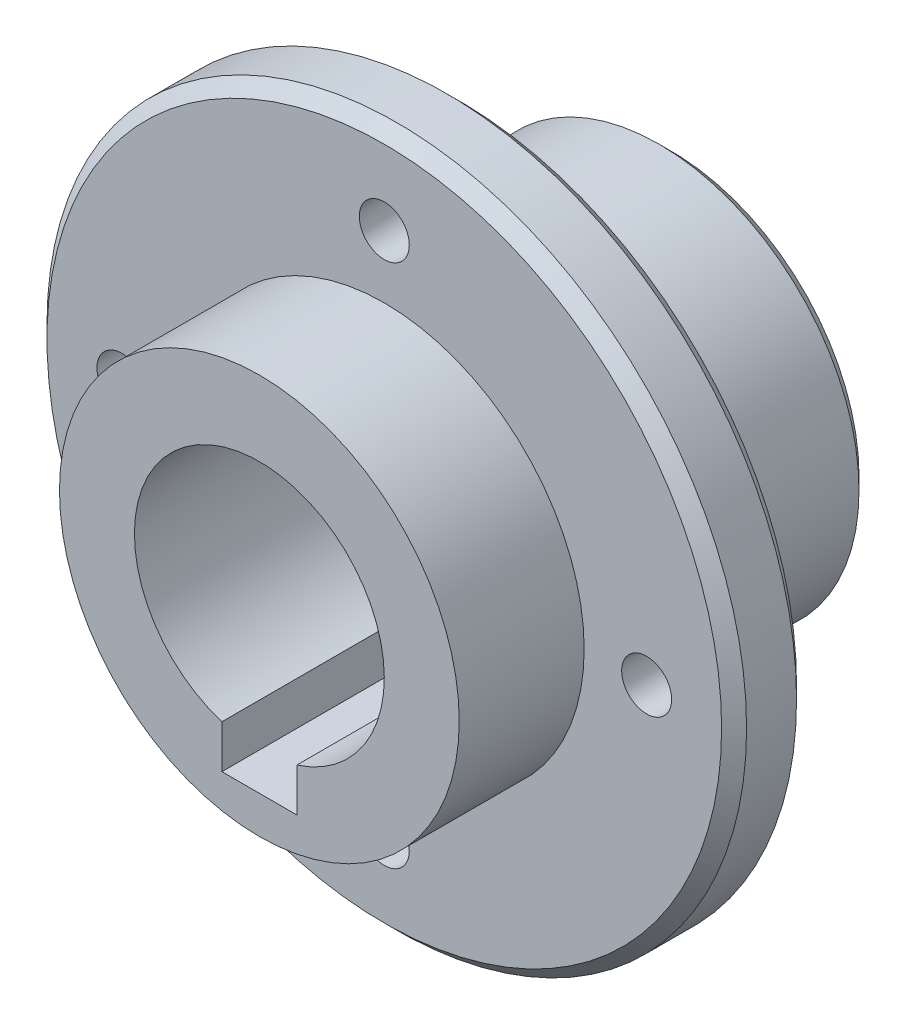
SolidWorks part; units mm, degrees
material "合金钢 (SS)"
ref_plane "前视基准面" through (0, 0, 0) normal (0, 0, 1) x (1, 0, 0)
ref_plane "上视基准面" through (0, 0, 0) normal (0, 1, 0) x (1, 0, 0)
ref_plane "右视基准面" through (0, 0, 0) normal (1, 0, 0) x (0, 0, -1)
sketch "草图1" plane through (0, 0, 0) normal (0, 0, 1) x (1, 0, 0)
  circle A0 centre (0, 0) radius 16
extrude "凸台-拉伸1" add sketch "草图1" along normal blind 13 contours A0
sketch "草图2" plane through (0, 0, 13) normal (0, 0, 1) x (1, 0, 0)
  circle A0 centre (0, 0) radius 16
extrude "凸台-拉伸2" add sketch "草图2" along normal blind 4
sketch "草图3" plane through (0, 0, 17) normal (0, 0, 1) x (1, 0, 0)
  circle A0 centre (0, 0) radius 28
extrude "凸台-拉伸3" add sketch "草图3" along normal blind 6 contours A0
sketch "草图4" plane through (0, 0, 23) normal (0, 0, 1) x (1, 0, 0)
  circle A0 centre (0, 0) radius 7
extrude "凸台-拉伸4" add sketch "草图4" along normal blind 5
sketch "草图6" plane through (0, 0, 17) normal (0, 0, -1) x (-1, 0, 0)
  circle A0 centre (0, 21) radius 2
  point P2 (0, 0)
  point P3 (0, 0)
  point P4 (0, 0)
  point P5 (0, 0)
extrude "切除-拉伸1" cut sketch "草图6" against normal blind 10
sketch "草图7" plane through (0, 0, 0) normal (0, 0, -1) x (-1, 0, 0)
  circle A0 centre (0, 0) radius 10
extrude "切除-拉伸2" cut sketch "草图7" against normal blind 60
pattern_circular "阵列(圆周)2" count 4 over 360 about axis through (0, 0, 0) along (0, 0, 1) of "切除-拉伸1"
chamfer "倒角3" distance 1 angle 45 1 edges at (28, 0, 23)
chamfer "倒角4" distance 1 angle 45 1 edges at (28, 0, 17)
chamfer "倒角6" distance 1 angle 45 1 edges at (16, 0, 0)
sketch "草图8" plane through (0, 0, 23) normal (0, 0, 1) x (1, 0, 0)
  circle A0 centre (0, 0) radius 16
  circle A1 centre (0, 0) radius 10
extrude "凸台-拉伸5" add sketch "草图8" along normal blind 10
sketch "草图9" plane through (0, 0, 0) normal (0, 1, 0) x (1, 0, 0)
  line L1 (-16, -33) -> (16, -33) construction
  line L5 (15, 0) -> (-15, 0) construction
  line L6 (-3, 0) -> (0, 0)
  line L7 (0, 0) -> (3, 0)
  line L8 (3, 0) -> (3, -33)
  line L9 (3, -33) -> (-3, -33)
  line L10 (-3, 0) -> (-3, -33)
  dimension "D1" = 0
  dimension "D2" = 0
  dimension "D3" = 3
  dimension "D4" = 3
extrude "切除-拉伸3" cut sketch "草图9" against normal blind 13 from offset 0
